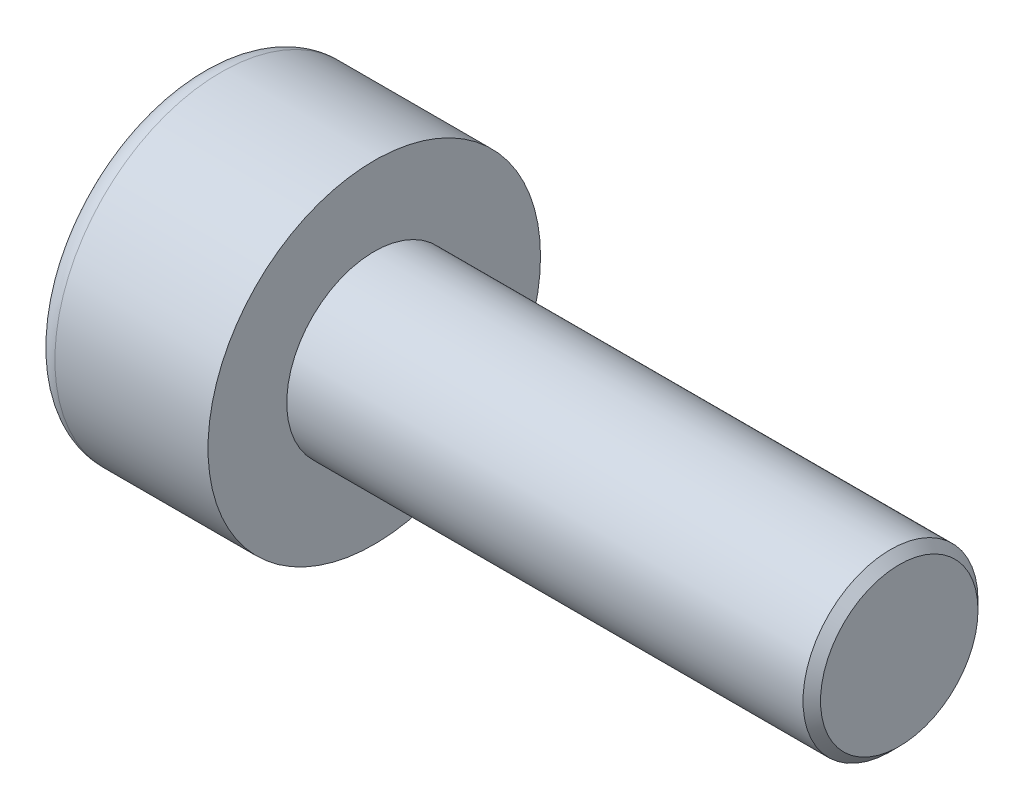
SolidWorks part; units mm, degrees
material "合金钢"
ref_plane "Front" through (0, 0, 0) normal (0, 0, 1) x (1, 0, 0)
ref_plane "Top" through (0, 0, 0) normal (0, 1, 0) x (1, 0, 0)
ref_plane "Right" through (0, 0, 0) normal (1, 0, 0) x (0, 0, -1)
sketch "Sketch1" plane through (0, 0, 0) normal (1, 0, 0) x (0, 0, -1)
  circle A0 centre (0, 0) radius 1.9
  dimension "dk" = 3.8
extrude "BaseHead" add sketch "Sketch1" along normal blind 2
sketch "Sketch2" plane through (2, 0, 0) normal (1, 0, 0) x (0, 0, -1)
  circle A0 centre (0, 0) radius 1
  dimension "d" = 2
extrude "BaseBody" add sketch "Sketch2" along normal blind 6
cosmetic thread "ThreadCosmetic1" [suppressed] parameters "b"=5, "D2"=1.567
sketch "Sketch3" plane through (0, 0, 0) normal (1, 0, 0) x (0, 0, -1)
  line L1 (0.866, 0) -> (0.433, 0.75)
  line L2 (0.433, 0.75) -> (-0.433, 0.75)
  line L3 (-0.433, 0.75) -> (-0.866, 0)
  line L4 (-0.866, 0) -> (-0.433, -0.75)
  line L5 (-0.433, -0.75) -> (0.433, -0.75)
  line L6 (0.433, -0.75) -> (0.866, 0)
  circle A0 centre (0, 0) radius 0.75 construction
  dimension "s" = 1.5
  dimension "e" = 1.7321
extrude "HexagonSocket" cut sketch "Sketch3" along normal blind 1
sketch "Sketch4" plane through (-4.1961, 0.75, 0) normal (0, 0, 1) x (-1, 0, 0)
  line L0 (-5.1961, 1.5) -> (-5.6292, 0.75)
  line L2 (-5.6292, 0.75) -> (-5.1961, 0.75)
  line L3 (-5.1961, 0.75) -> (-5.1961, 1.5)
  line L4 (-5.0351, 0.75) -> (0.839, 0.75) construction
  line L5 (-12.1961, 0.75) -> (-6.1961, 0.75) construction
  line L6 (-6.1961, 0.75) -> (-4.1961, 0.75) construction
  dimension "m" = 60
revolve "Cut-Revolve1" cut sketch "Sketch4" angle 360 about L4
fillet "HeadFillet" [suppressed] radius 0.1
fillet "TopFillet" radius 0.25 1 edges at (0, 0, -1.9)
chamfer "Chamfer1" distance 0.1 angle 45 1 edges at (8, 0, -1)
sketch "Sketch5" plane through (0, 0, 0) normal (0, 0, 1) x (1, 0, 0)
  line L0 (7.9, 0.8125) -> (8.0083, 1)
  line L1 (8.0083, 1) -> (8.0083, 1.2165)
  line L2 (8.0083, 1.2165) -> (7.7918, 1.2165)
  line L3 (7.7918, 1.2165) -> (7.7918, 1)
  line L4 (7.7918, 1) -> (7.9, 0.8125)
  line L5 (0, 0) -> (7.8886, 0) construction
  line L6 (7.9, -1) -> (7.9, 1) construction
  dimension "D1" = 2
  dimension "D2" = 0.2165
revolve "Cut-Revolve10" [suppressed] cut sketch "Sketch5" angle 360 about L5
pattern_linear "LPattern10" [suppressed] count 19 spacing 0.2598 along (1, 0, 0)
equation "\"r1@TopFillet\" = \"d@Sketch2\" / 8"
equation "\"D1@Chamfer1\" = \"r@HeadFillet\""
equation "\"D1@Sketch5\" = \"d@Sketch2\""
equation "\"D2@Sketch5\" =  ( \"d@Sketch2\" - \"D2@ThreadCosmetic1\" )  / 2"
equation "\"D3@LPattern10\" = \"D2@Sketch5\" * 1.2"
equation "\"D1@LPattern10\" = \"b@ThreadCosmetic1\" / \"D3@LPattern10\""
